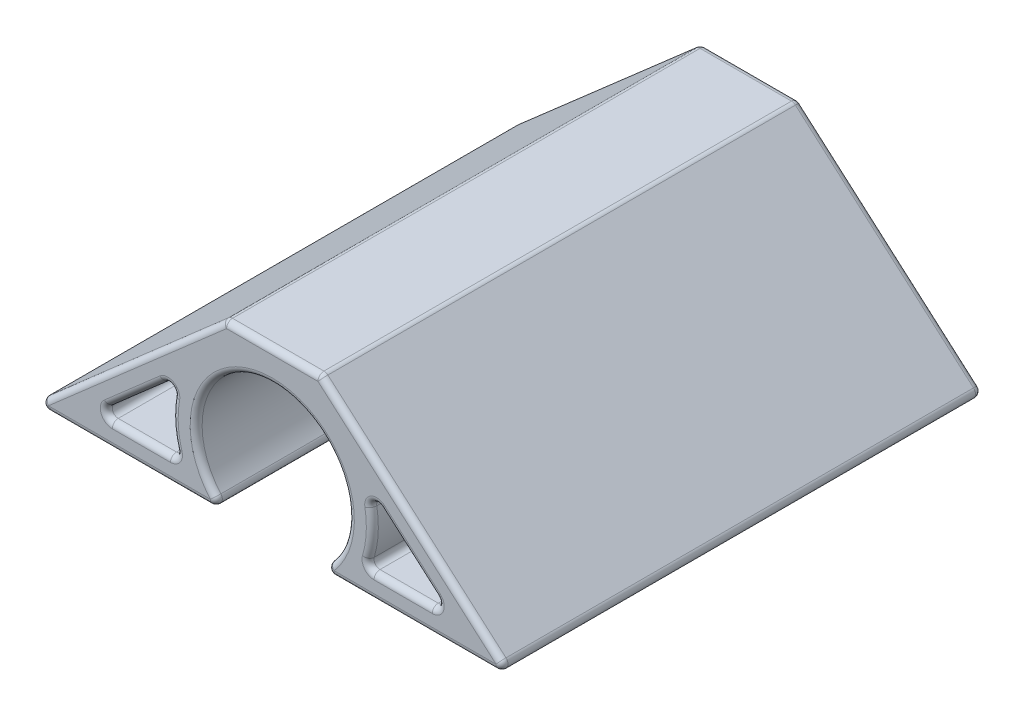
SolidWorks part; units mm, degrees
ref_plane "Front Plane" through (0, 0, 0) normal (0, 0, 1) x (1, 0, 0)
ref_plane "Top Plane" through (0, 0, 0) normal (0, 1, 0) x (1, 0, 0)
ref_plane "Right Plane" through (0, 0, 0) normal (1, 0, 0) x (0, 0, -1)
sketch "Sketch1" plane through (0, 0, 0) normal (0, 0, 1) x (1, 0, 0)
  line L0 (0, 6.9998) -> (0, -6.4819) construction
  line L1 (-6.0674, 0) -> (9.6842, 0) construction
  line L2 (1.9572, -2.5) -> (10, -2.5)
  line L3 (10, -2.5) -> (2, 4.5)
  line L4 (2, 4.5) -> (0, 4.5)
  line L5 (0, 4.5) -> (0, 4.175)
  line L6 (3.8962, -1.5) -> (7.3386, -1.5)
  line L7 (7.3386, -1.5) -> (3.8892, 1.5182)
  line L8 (-1.9572, -2.5) -> (-10, -2.5)
  line L9 (7.3386, -1.5) -> (1.6243, 3.5) construction
  line L10 (1.6243, 3.5) -> (0.7378, 3.5) construction
  line L11 (0.7378, 3.5) -> (0.7378, 3.5) construction
  line L12 (0, -1.5) -> (7.3386, -1.5) construction
  line L13 (-7.3386, -1.5) -> (-3.8892, 1.5182)
  line L14 (-3.8962, -1.5) -> (-7.3386, -1.5)
  line L15 (-10, -2.5) -> (-2, 4.5)
  line L16 (-2, 4.5) -> (0, 4.5)
  line L18 (0, -2.5) -> (10, -2.5) construction
  arc A0 (1.9572, -2.5) -> (-1.9572, -2.5) centre (0, 0) ccw
  arc A1 (-3.8892, 1.5182) -> (-3.8962, -1.5) centre (0, 0) ccw
  arc A2 (3.8962, -1.5) -> (3.8892, 1.5182) centre (0, 0) ccw
  point P1 (0, 0)
  point P12 (0, 0)
  dimension "D1" = 6.35
  dimension "D2" = 8.35
  dimension "D3" = 8.0428
  dimension "D5" = 2
  dimension "D6" = 2.5
  dimension "D7" = 4.5
  dimension "D4" = 1
extrude "Boss-Extrude1" add sketch "Sketch1" along normal blind 20
fillet "Fillet1" radius 0.25 12 edges at (-2, 4.5, 10) (2, 4.5, 10) (3.8892, 1.5182, 10) (-3.8892, 1.5182, 10) (-1.9572, -2.5, 10) (10, -2.5, 10) (1.9572, -2.5, 10) (-10, -2.5, 10) (7.3386, -1.5, 10) (-3.8962, -1.5, 10) (3.8962, -1.5, 10) (-7.3386, -1.5, 10)
fillet "Fillet2" radius 0.25 48 edges at (4.2332, 0.995, 0) (5.6793, -0.0482, 0) (6.9072, -1.3379, 0) (5.459, -1.5, 0) (4.0446, -1.3997, 0) (4.1687, -0.2291, 0) (-4.2332, 0.995, 0) (-4.1687, -0.2291, 0) (-4.0446, -1.3997, 0) (-5.459, -1.5, 0) (-6.9072, -1.3379, 0) (-5.6793, -0.0482, 0) (-9.5687, -2.3379, 0) (-5.9585, -2.5, 0) (-2.3547, -2.3535, 0) (0, 3.175, 0) (2.3547, -2.3535, 0) (5.9585, -2.5, 0) (9.5687, -2.3379, 0) (5.785, 1.1881, 0) (1.994, 4.484, 0) (0, 4.5, 0) (-1.994, 4.484, 0) (-5.785, 1.1881, 0) (6.9072, -1.3379, 20) (5.6793, -0.0482, 20) (4.2332, 0.995, 20) (4.1687, -0.2291, 20) (4.0446, -1.3997, 20) (5.459, -1.5, 20) (-4.0446, -1.3997, 20) (-4.1687, -0.2291, 20) (-4.2332, 0.995, 20) (-5.6793, -0.0482, 20) (-6.9072, -1.3379, 20) (-5.459, -1.5, 20) (1.994, 4.484, 20) (5.785, 1.1881, 20) (9.5687, -2.3379, 20) (5.9585, -2.5, 20) (2.3547, -2.3535, 20) (0, 3.175, 20) (-2.3547, -2.3535, 20) (-5.9585, -2.5, 20) (-9.5687, -2.3379, 20) (-5.785, 1.1881, 20) (-1.994, 4.484, 20) (0, 4.5, 20)
